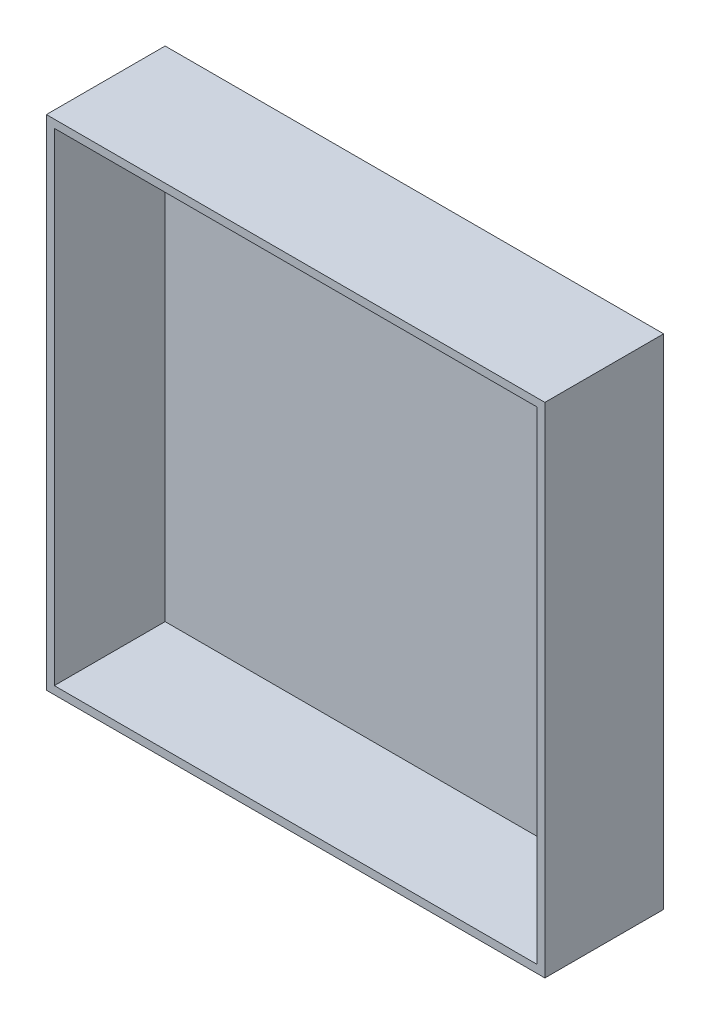
SolidWorks part; units mm, degrees
ref_plane "前视基准面" through (0, 0, 0) normal (0, 0, 1) x (1, 0, 0)
ref_plane "上视基准面" through (0, 0, 0) normal (0, 1, 0) x (1, 0, 0)
ref_plane "右视基准面" through (0, 0, 0) normal (1, 0, 0) x (0, 0, -1)
sketch "草图1" plane through (0, 0, 0) normal (0, 0, 1) x (1, 0, 0)
  line L0 (29.8731, -0.2667) -> (29.8731, -60.2414) construction
  line L1 (-0.6119, -60.7391) -> (60.3581, -60.7391)
  line L2 (-0.6119, -60.7391) -> (-0.6119, 0.2309)
  line L3 (-0.6119, 0.2309) -> (60.3581, 0.2309)
  line L4 (60.3581, -60.7391) -> (60.3581, 0.2309)
  line L5 (-0.1143, -0.2667) -> (59.8604, -0.2667) construction
  line L6 (-0.1143, -0.2667) -> (-0.1143, -60.2414) construction
  line L7 (-0.1143, -60.2414) -> (59.8604, -60.2414) construction
  line L8 (59.8604, -0.2667) -> (59.8604, -60.2414) construction
  line L9 (-0.1143, -30.2541) -> (59.8604, -30.2541) construction
  line L10 (29.8731, 0.2309) -> (29.8731, -60.7391) construction
  point P16 (29.8731, -30.2541)
  point P17 (29.8731, -30.2541)
  dimension "D1" = 60.97
extrude "拉伸-薄壁1" add sketch "草图1" along normal blind 14 from offset 5 thin offset against normal yes
sketch "草图3" plane through (0, 0, -5) normal (0, 0, -1) x (-1, 0, 0)
  line L1 (-61.3581, 1.2309) -> (1.6119, 1.2309)
  line L2 (-61.3581, 1.2309) -> (-61.3581, -61.7391)
  line L3 (-61.3581, -61.7391) -> (1.6119, -61.7391)
  line L4 (1.6119, 1.2309) -> (1.6119, -61.7391)
extrude "凸台-拉伸1" add sketch "草图3" along normal blind 1
